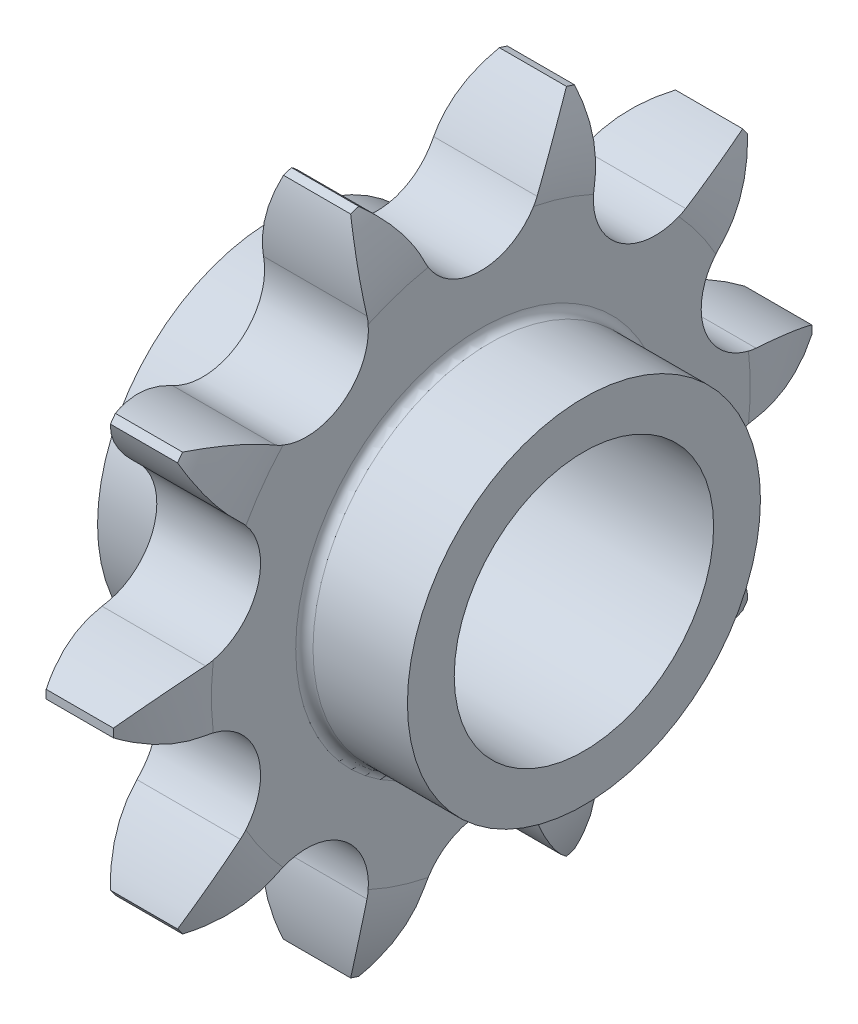
SolidWorks part; units mm, degrees
ref_plane "Plane1" through (0, 0, 0) normal (0, 0, 1) x (1, 0, 0)
ref_plane "Plane2" through (0, 0, 0) normal (0, 1, 0) x (1, 0, 0)
ref_plane "Plane3" through (0, 0, 0) normal (1, 0, 0) x (0, 0, -1)
sketch "Clipboard" plane through (0, 0, 0) normal (0, 1, 0) x (1, 0, 0)
  line L0 (0, 0) -> (12.5071, -2.2053)
  line L1 (-15, 0) -> (100, 0) construction
  line L2 (0, 0) -> (-0.8416, 0.9512)
  line L3 (0, 0) -> (-11.863, 4.5341)
  line L4 (0, 0) -> (3.0529, 0.5383)
  line L5 (0, 0) -> (-20.1445, -7.5133)
  line L6 (0, 0) -> (-5.9685, -4.027)
  line L7 (-0.8416, 0.9512) -> (20.2639, 5.0536)
  line L8 (-76.2, 38.1) -> (-73.4, 38.1)
  line L9 (-73.4259, 41.6592) -> (-72.8306, 41.7344)
  line L10 (-73.4741, 12.7512) -> (-59.5541, 12.7512)
  circle A0 centre (0, 0) radius 4.255
  circle A1 centre (0, 0) radius 12.2483
  circle A2 centre (0, 0) radius 13.425
  dimension "Dr" = 8.51
  dimension "MHD" = 24.4966
  dimension "Hub_dia" = 26.85
  dimension "Num_teeth" = 10
  dimension "Pitch" = 12.7
  dimension "Width" = 3.1
  dimension "Side_relief" = 1.27
  dimension "Side_radius" = 12.7
  dimension "Overall_len" = 21.5
  dimension "Show_teeth" = 10
  dimension "Thickness" = 7.2
  dimension "OAL" = 21.5005
  dimension "T_dim" = 2.8
  dimension "Fillet_rad" = 0.6
  dimension "Face_width" = 7.2
  dimension "Num_strands" = 1
  dimension "Transv_pitch" = 13.92
  dimension "Plate_wid" = 11.8
sketch "BasProSke" plane through (0, 0, 0) normal (0, 1, 0) x (1, 0, 0)
  line L0 (-10, 0) -> (60, 0) construction
  line L1 (0, 0) -> (0, 18.6957)
  line L2 (0, 0) -> (7.2, 0)
  line L3 (7.2, 0) -> (7.2, 18.6957)
  line L4 (5.93, 24.2315) -> (1.27, 24.2315)
  arc A0 (0, 18.6957) -> (1.27, 24.2315) centre (12.7, 18.6957) cw
  arc A1 (7.2, 18.6957) -> (5.93, 24.2315) centre (-5.5, 18.6957) ccw
  dimension "D1" = 12.7
  dimension "G1" = 1.27
  dimension "G2" = 1.27
  dimension "Diameter" = 48.4631
  dimension "Thickness" = 7.2
revolve "Base-Revolve" add sketch "BasProSke" angle 360 about L0
sketch "TooCutSke" plane through (0, 0, 0) normal (1, 0, 0) x (0, 0, -1)
  line L0 (0, 20.5916) -> (3.9106, 18.8094) construction
  line L1 (0, 0) -> (0, 107) construction
  line L2 (0, 20.5916) -> (-10, 20.5916) construction
  line L3 (0, 20.5916) -> (-3.9106, 18.8094) construction
  arc A0 (3.9106, 18.8094) -> (7.6796, 23.509) centre (15.0616, 13.7276) cw
  arc A1 (3.9106, 18.8094) -> (-3.9106, 18.8094) centre (0, 20.5916) cw
  arc A2 (-3.9106, 18.8094) -> (-7.6796, 23.509) centre (-15.0616, 13.7276) ccw
  arc A3 (7.6796, 23.509) -> (-7.6796, 23.509) centre (0, 0) ccw
  dimension "R1" = 4.2976
  dimension "R2" = 12.2544
  dimension "Overcut" = 24.7315
  dimension "Seat_radius" = 20.5916
  dimension "X" = 131
extrude "ToothCut" cut sketch "TooCutSke" along normal through all
pattern_circular "TeethCuts" count 10 every 36 about axis through (-10, 0, 0) along (1, 0, 0) of "ToothCut"
sketch "HubNeaOneSke" plane through (0, 0, 0) normal (-1, 0, 0) x (0, 0, 1)
  circle A0 centre (0, 0) radius 12.2483
  dimension "Diameter" = 24.4966
extrude "HubNearOne" [suppressed] add sketch "HubNeaOneSke" along normal blind 14.3005
fillet "HubNearOneFillet" [suppressed] radius 0.6
sketch "HubNeaBotSke" plane through (0, 0, 0) normal (-1, 0, 0) x (0, 0, 1)
  circle A0 centre (0, 0) radius 12.2483
  dimension "Diameter" = 24.4966
extrude "HubNearBoth" add sketch "HubNeaBotSke" along normal blind 7.1502
fillet "HubNearBothFillet" radius 0.6 1 edges at (0, 0, -12.2483)
ref_plane "FarPln" through (7.2, 0, 0) normal (1, 0, 0) x (0, 0, -1)
sketch "HubFarSke" plane through (7.2, 0, 0) normal (1, 0, 0) x (0, 0, -1)
  circle A0 centre (0, 0) radius 12.2483
  dimension "Diameter" = 24.4966
extrude "HubFar" add sketch "HubFarSke" along normal blind 7.1502
fillet "HubFarFillet" radius 0.6 1 edges at (7.2, 0, 12.2483)
sketch "BorSke" plane through (0, 0, 0) normal (1, 0, 0) x (0, 0, -1)
  circle A0 centre (0, 0) radius 9
  dimension "Diameter" = 18
extrude "Bore" cut sketch "BorSke" along normal mid plane 43.001
sketch "KeySke" plane through (0, 0, 0) normal (1, 0, 0) x (0, 0, -1)
  line L0 (-3, 0) -> (-3, 11.8)
  line L1 (-3, 11.8) -> (3, 11.8)
  line L2 (3, 11.8) -> (3, 0)
  line L3 (0, 0) -> (0, 34) construction
  line L4 (-3, 0) -> (3, 0)
  dimension "Offset" = 11.8
  dimension "Width" = 6
extrude "Keyway" [suppressed] cut sketch "KeySke" along normal mid plane 43.001
pattern_circular "Keyway2" [suppressed] count 2 every 90 about axis through (-10, 0, 0) along (1, 0, 0)
equation "' \"Pitch@Clipboard\" = 12.7"
equation "' \"Num_strands@Clipboard\" = 1"
equation "' \"Num_teeth@Clipboard\" = 9"
equation "' \"Hub_dia@Clipboard\" = 50"
equation "' \"Overall_len@Clipboard\" = 3"
equation "' \"Diameter@BorSke\" = 12"
equation "' \"T_dim@Clipboard\" = 1"
equation "' \"Width@KeySke\" = 2"
equation "' \"Dr@Clipboard\" = 8.51"
equation "' \"Face_width@Clipboard\" = 7.2"
equation "' \"Side_radius@Clipboard\" = 12.7"
equation "' \"Side_relief@Clipboard\" = 1.27"
equation "' \"Transv_pitch@Clipboard\" = 13.92"
equation "' \"Show_teeth@Clipboard\" = 9"
equation "' \"Fillet_rad@Clipboard\" = 0.6"
equation "' \"Plate_wid@Clipboard\" = 11.8"
equation "\"Num_teeth@Clipboard\" = int( \"Num_teeth@Clipboard\" )"
equation "\"Num_teeth@Clipboard\" = ((sgn( \"Num_teeth@Clipboard\" - 5.0)+1)*( \"Num_teeth@Clipboard\" - 5.0))/2 +5.0"
equation "\"Num_teeth@Clipboard\" = ((sgn( \"Num_teeth@Clipboard\" - 200.0)-1)*( \"Num_teeth@Clipboard\" - 200.0))/-2 +200.0"
equation "\"MHD@Clipboard\" = \"Pitch@Clipboard\" * (1.0 / tan(3.14159265 / \"Num_teeth@Clipboard\" )) - 1.05 * \"Plate_wid@Clipboard\" - 2.0 * \"Fillet_rad@Clipboard\" - 1.0"
equation "\"Thickness@Clipboard\"  = \"Face_width@Clipboard\" + (\"Num_strands@Clipboard\" - 1) * \"Transv_pitch@Clipboard\""
equation "\"OAL@Clipboard\" = \"Thickness@Clipboard\" + 2 * \"Fillet_rad@Clipboard\" + 1"
equation "\"MHD@Clipboard\" = ((sgn( \"MHD@Clipboard\" - \"Hub_dia@Clipboard\" )-1)*( \"MHD@Clipboard\" - \"Hub_dia@Clipboard\" ))/-2+ \"Hub_dia@Clipboard\""
equation "\"OAL@Clipboard\" = ((sgn( \"OAL@Clipboard\" - \"Overall_len@Clipboard\" )+1)*( \"OAL@Clipboard\" - \"Overall_len@Clipboard\" ))/2 + \"Overall_len@Clipboard\" + 0.0005"
equation "\"Num_teeth@TeethCuts\" = int( \"Show_teeth@Clipboard\" ) + 1"
equation "\"Num_teeth@TeethCuts\" = ((sgn( \"Num_teeth@TeethCuts\" - \"Num_teeth@Clipboard\" )-1)*( \"Num_teeth@TeethCuts\" - \"Num_teeth@Clipboard\" ))/-2+ \"Num_teeth@Clipboard\""
equation "\"Num_teeth@TeethCuts\" = ((sgn( \"Num_teeth@TeethCuts\" - 2.0)+1)*( \"Num_teeth@TeethCuts\" - 2.0))/2 +2.0"
equation "\"Angle@TeethCuts\" = 360.0 / \"Num_teeth@Clipboard\""
equation "\"Seat_radius@TooCutSke\" = ( \"Pitch@Clipboard\" / 2.0) / sin(3.14159265 / \"Num_teeth@Clipboard\" ) - \"Dr@Clipboard\" / 2.0 + \"Dr@Clipboard\" * 0.505"
equation "\"R1@TooCutSke\"  = \"Dr@Clipboard\" * 0.505"
equation "\"X@TooCutSke\" = 140.0 - (90.0 / \"Num_teeth@Clipboard\")"
equation "\"R2@TooCutSke\" = 0.12 * \"Dr@Clipboard\" * ( \"Num_teeth@Clipboard\" + 2.0)"
equation "\"Overcut@TooCutSke\" = 0.5 + 0.625 * \"Pitch@Clipboard\" - 0.5 * \"Dr@Clipboard\"  +  \"Pitch@Clipboard\" / 2.0 / sin(3.14159265 / \"Num_teeth@Clipboard\" )"
equation "\"Diameter@BasProSke\" = 2.0 * ( 0.625 * \"Pitch@Clipboard\" - 0.5 * \"Dr@Clipboard\"  +  \"Pitch@Clipboard\" / 2.0 / sin(3.14159265 / \"Num_teeth@Clipboard\" ))"
equation "\"Thickness@BasProSke\"  = \"Thickness@Clipboard\""
equation "\"G1@BasProSke\" =  \"Side_relief@Clipboard\""
equation "\"G2@BasProSke\" =  \"Side_relief@Clipboard\""
equation "\"D1@BasProSke\" =  \"Side_radius@Clipboard\""
equation "\"Diameter@HubNeaOneSke\" = \"MHD@Clipboard\""
equation "\"Length@HubNearOne\" = \"OAL@Clipboard\" - \"Thickness@BasProSke\""
equation "\"Diameter@HubNeaBotSke\" = \"MHD@Clipboard\""
equation "\"Length@HubNearBoth\" = ( \"OAL@Clipboard\" - \"Thickness@BasProSke\" ) / 2.0"
equation "\"D1@HubNearOneFillet\" = \"Fillet_rad@Clipboard\""
equation "\"D1@HubNearBothFillet\" = \"Fillet_rad@Clipboard\""
equation "\"Thickness@FarPln\" = \"Thickness@BasProSke\""
equation "\"Diameter@HubFarSke\" = \"MHD@Clipboard\""
equation "\"Length@HubFar\" = ( \"OAL@Clipboard\" - \"Thickness@BasProSke\" ) / 2.0"
equation "\"D1@HubFarFillet\" = \"Fillet_rad@Clipboard\""
equation "\"D1@Bore\" = \"OAL@Clipboard\" * 2.0"
equation "\"D1@Keyway\" = \"OAL@Clipboard\" * 2.0"
equation "\"Offset@KeySke\" = \"T_dim@Clipboard\" + \"Diameter@BorSke\" / 2.0"
